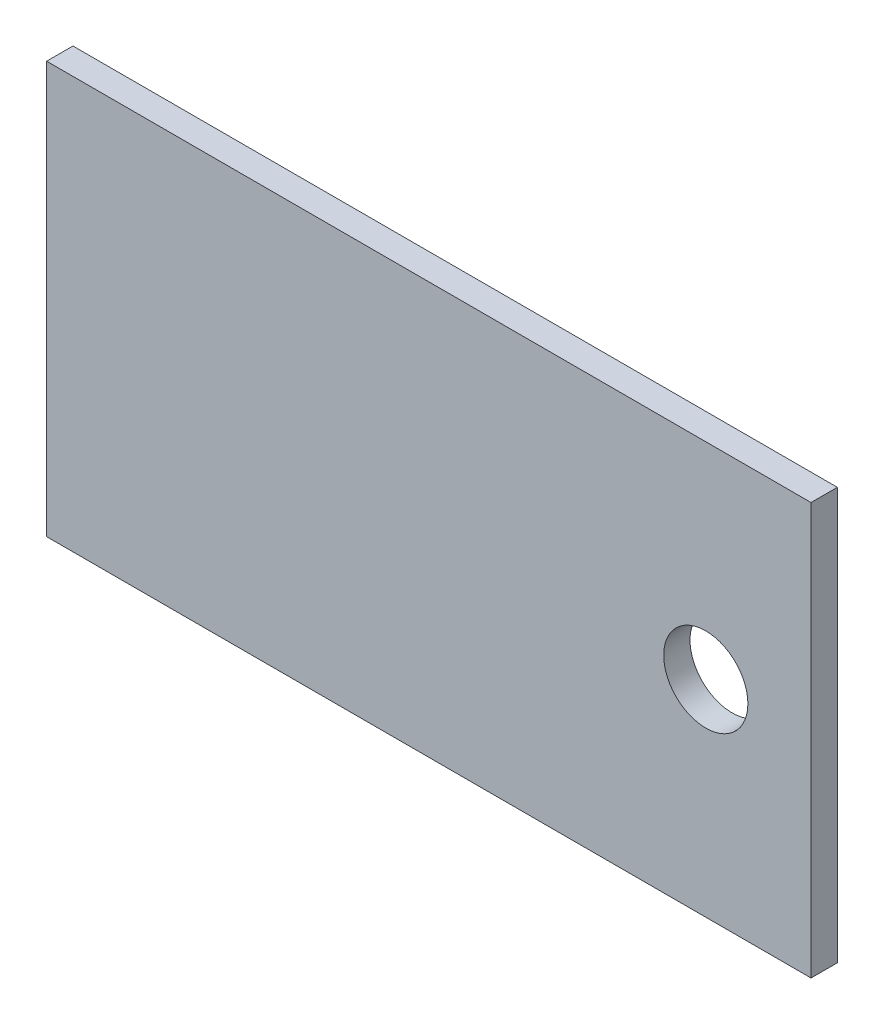
SolidWorks part; units mm, degrees
ref_plane "Ön Düzlem" through (0, 0, 0) normal (0, 0, 1) x (1, 0, 0)
ref_plane "Üst Düzlem" through (0, 0, 0) normal (0, 1, 0) x (1, 0, 0)
ref_plane "Sağ Düzlem" through (0, 0, 0) normal (1, 0, 0) x (0, 0, -1)
sketch "Çizim1" plane through (0, 0, 0) normal (0, 0, 1) x (1, 0, 0)
  line L0 (0, 0) -> (0, 31.3)
  line L1 (0, 31.3) -> (58.1, 31.3)
  line L2 (58.1, 31.3) -> (58.1, 0)
  line L3 (58.1, 0) -> (0, 0)
extrude "Yükseklik-Ekstrüzyon1" add sketch "Çizim1" along normal blind 2
sketch "Çizim2" plane through (0, 0, 0) normal (0, 0, 1) x (1, 0, 0)
  circle A0 centre (50.1, 15.65) radius 3.2
extrude "Kes-Ekstrüzyon1" cut sketch "Çizim2" along normal blind 2
